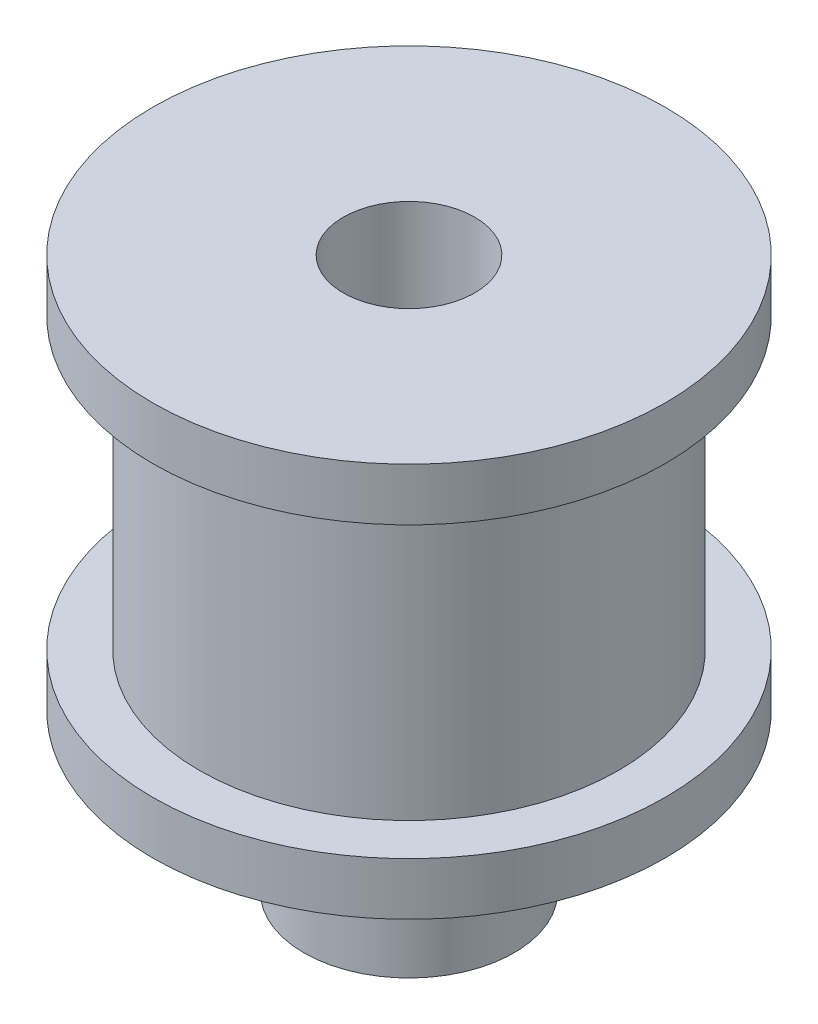
SolidWorks part; units mm, degrees
ref_plane "Plan de face" through (0, 0, 0) normal (0, 0, 1) x (1, 0, 0)
ref_plane "Plan de dessus" through (0, 0, 0) normal (0, 1, 0) x (1, 0, 0)
ref_plane "Plan de droite" through (0, 0, 0) normal (1, 0, 0) x (0, 0, -1)
sketch "Esquisse1" plane through (0, 0, 0) normal (0, 0, 1) x (1, 0, 0)
  line L0 (0, 0) -> (0, 28.0434) construction
  line L1 (0, 0) -> (2.5, 0) construction
  line L2 (2.5, 0) -> (2.5, 21)
  line L3 (2.5, 21) -> (9.75, 21)
  line L4 (9.75, 21) -> (9.75, 19)
  line L5 (9.75, 19) -> (7.975, 19)
  line L6 (7.975, 19) -> (7.975, 8)
  line L7 (7.975, 8) -> (9.75, 8)
  line L8 (9.75, 8) -> (9.75, 6)
  line L9 (9.75, 6) -> (4, 6)
  line L10 (4, 6) -> (4, 0)
  line L11 (4, 0) -> (2.5, 0)
  line L12 (9.75, 8) -> (9.75, 19) construction
  dimension "D1" = 5
  dimension "D2" = 8
  dimension "D3" = 19.5
  dimension "D4" = 15.95
  dimension "D5" = 2
  dimension "D6" = 15
  dimension "D7" = 21
revolve "Révolution1" add sketch "Esquisse1" angle 360 about L0
